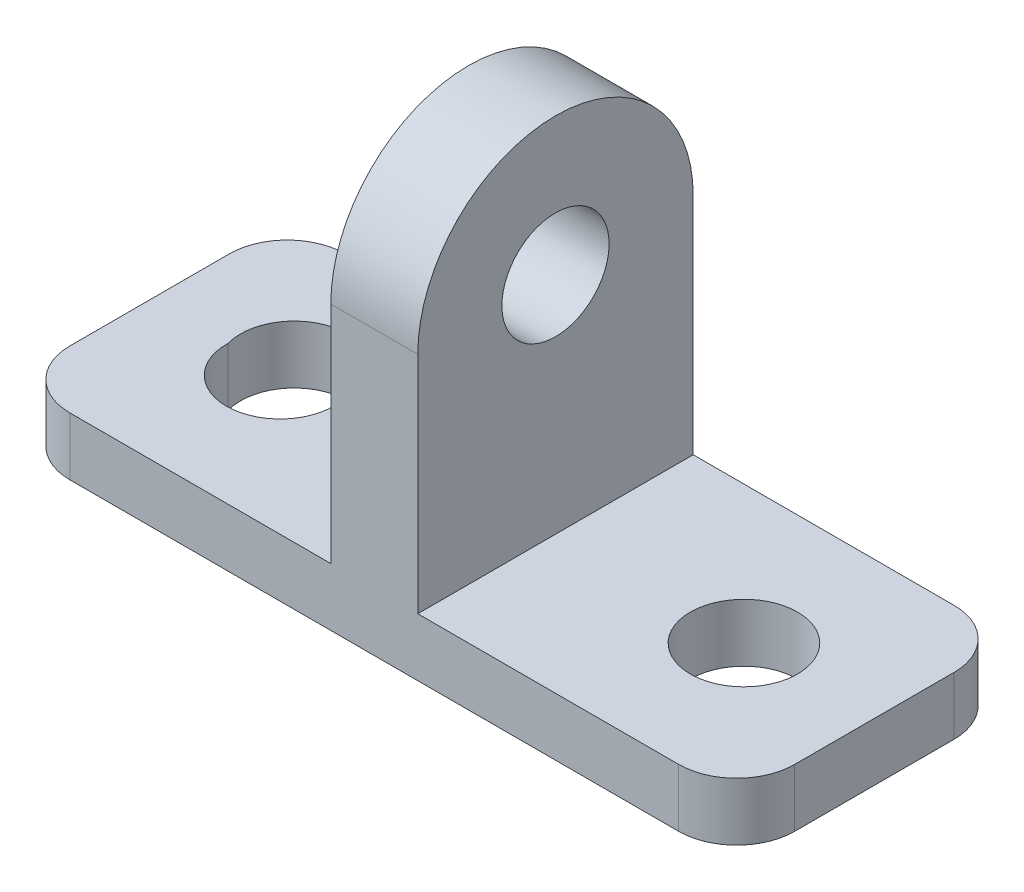
SolidWorks part; units mm, degrees
ref_plane "Front" through (0, 0, 0) normal (0, 0, 1) x (1, 0, 0)
ref_plane "Top" through (0, 0, 0) normal (0, 1, 0) x (1, 0, 0)
ref_plane "Right" through (0, 0, 0) normal (1, 0, 0) x (0, 0, -1)
sketch "Sketch1" plane through (0, 0, 0) normal (0, 0, 1) x (1, 0, 0)
  line L1 (-12.5, 7.25) -> (12.5, 7.25)
  line L2 (-12.5, 7.25) -> (-12.5, -7.25)
  line L3 (-12.5, -7.25) -> (12.5, -7.25)
  line L4 (12.5, 7.25) -> (12.5, -7.25)
  line L5 (-12.5, 7.25) -> (12.5, -7.25) construction
  line L6 (-12.5, -7.25) -> (12.5, 7.25) construction
  point P0 (0, 0)
  dimension "D1" = 25
  dimension "D2" = 14.5
extrude "Boss-Extrude1" add sketch "Sketch1" along normal blind 9.5
sketch "Sketch2" plane through (12.5, 0, 0) normal (1, 0, 0) x (0, 0, -1)
  line L0 (-9.5, 7.25) -> (0, 7.25) construction
  line L1 (0, -7.25) -> (0, 7.25) construction
  line L3 (-9.5, 2.5) -> (-9.5, 8.25)
  line L4 (-9.5, 8.25) -> (0, 8.25)
  line L5 (0, 8.25) -> (0, 2.5)
  line L6 (-9.5, -7.25) -> (-9.5, 7.25) construction
  arc A0 (0, 2.5) -> (-9.5, 2.5) centre (-4.75, 2.5) ccw
  dimension "D1" = 1
extrude "Cut-Extrude1" cut sketch "Sketch2" against normal through all
sketch "Sketch3" plane through (0, 0, 9.5) normal (0, 0, 1) x (1, 0, 0)
  line L0 (12.5, 7.25) -> (-12.5, 7.25) construction
  line L5 (12.5, -7.25) -> (12.5, 2.5) construction
  line L6 (1.5, 7.25) -> (12.5, 7.25)
  line L7 (1.5, 7.25) -> (1.5, -5.25)
  line L8 (1.5, -5.25) -> (12.5, -5.25)
  line L9 (12.5, 7.25) -> (12.5, -5.25)
  line L10 (-12.5, 2.5) -> (-12.5, -7.25) construction
  line L11 (-1.5, 7.25) -> (-12.5, 7.25)
  line L12 (-1.5, 7.25) -> (-1.5, -5.25)
  line L13 (-1.5, -5.25) -> (-12.5, -5.25)
  line L14 (-12.5, 7.25) -> (-12.5, -5.25)
  line L17 (-12.5, -7.25) -> (12.5, -7.25) construction
  dimension "D1" = 3
  dimension "D2" = 2
extrude "Cut-Extrude2" cut sketch "Sketch3" against normal through all
sketch "Sketch4" plane through (1.5, 0, 0) normal (1, 0, 0) x (0, 0, -1)
  circle A0 centre (-4.75, 2.5) radius 1.85
  dimension "D1" = 3.7
extrude "Cut-Extrude3" cut sketch "Sketch4" against normal through all
fillet "Fillet1" radius 2 4 edges at (-12.5, -6.25, 0) (-12.5, -6.25, 9.5) (12.5, -6.25, 0) (12.5, -6.25, 9.5)
sketch "Sketch5" plane through (0, -5.25, 0) normal (0, 1, 0) x (1, 0, 0)
  line L0 (-12.5, -4.75) -> (-8, -4.75) construction
  line L1 (-12.5, -2) -> (-12.5, -7.5) construction
  line L2 (8, -4.75) -> (12.5, -4.75) construction
  line L6 (12.5, -2) -> (12.5, -7.5) construction
  circle A0 centre (-8, -4.75) radius 1.85
  circle A1 centre (8, -4.75) radius 1.85
  dimension "D2" = 3.7
  dimension "D1" = 4.5
extrude "Cut-Extrude4" cut sketch "Sketch5" against normal through all
extrude "Cut-Extrude10" cut sketch "Sketch11" against normal through all
sketch "Sketch11" plane through (-55.7, -5.25, -67.1103) normal (0, 1, 0) x (-1, 0, 0)
  circle A0 centre (-63.7, 71.8603) radius 1.85
  circle A1 centre (-47.6336, 71.3056) radius 1.85
